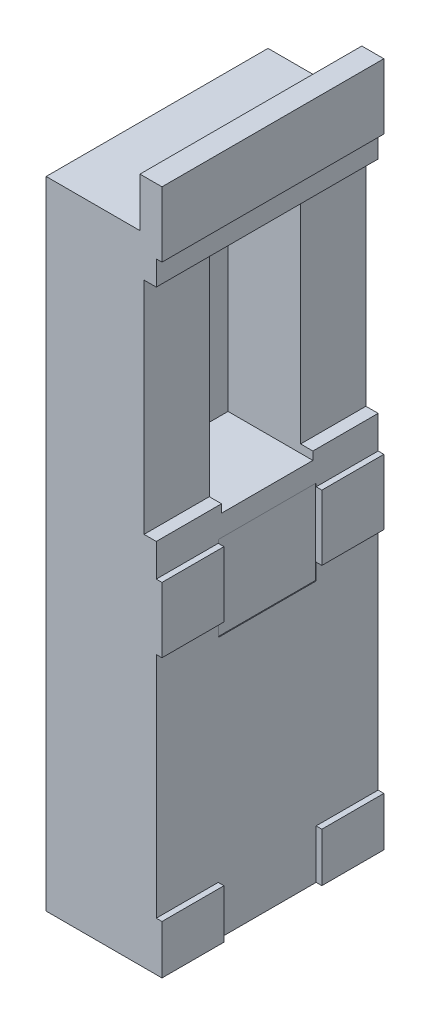
SolidWorks part; units mm, degrees
ref_plane "前视基准面" through (0, 0, 0) normal (0, 0, 1) x (1, 0, 0)
ref_plane "上视基准面" through (0, 0, 0) normal (0, 1, 0) x (1, 0, 0)
ref_plane "右视基准面" through (0, 0, 0) normal (1, 0, 0) x (0, 0, -1)
other "Configuration Table"
sketch "草图1" plane through (0, 0, 0) normal (0, 0, 1) x (1, 0, 0)
  line L0 (-10.2, 0) -> (-16.95, 0)
  line L1 (-16.95, 0) -> (-16.95, 54)
  line L2 (-16.95, 54) -> (-11.2, 54)
  line L3 (-11.2, 54) -> (-11.2, 57)
  line L4 (-11.2, 57) -> (-4.7, 57)
  line L5 (-4.7, 57) -> (-4.7, 53)
  line L6 (-4.7, 53) -> (-10.2, 53)
  line L7 (-10.2, 53) -> (-10.2, 51.5)
  line L8 (-10.2, 51.5) -> (-10.95, 51.5)
  line L9 (-10.95, 51.5) -> (-10.95, 38)
  line L10 (-10.95, 38) -> (-10.2, 38)
  line L11 (-10.2, 38) -> (-10.2, 36)
  line L12 (-10.2, 36) -> (-4.7, 36)
  line L13 (-4.7, 36) -> (-4.7, 32)
  line L14 (-4.7, 32) -> (-10.2, 32)
  line L15 (-10.2, 32) -> (-10.2, 0)
  dimension "x0" = 10.2
  dimension "x1" = 16.95
  dimension "x3" = 11.2
  dimension "x5" = 4.7
  dimension "x7" = 10.2
  dimension "x9" = 10.95
  dimension "x11" = 10.2
  dimension "x13" = 4.7
  dimension "y2" = 54
  dimension "y4" = 57
  dimension "y6" = 53
  dimension "y8" = 51.5
  dimension "y10" = 38
  dimension "y12" = 36
  dimension "y14" = 32
extrude "Guide_and_solid_stops" add sketch "草图1" along normal blind 13.6
ref_plane "Channel_midplane" through (0, 0, 6.8) normal (0, 0, 1) x (1, 0, 0)
sketch "草图3" plane through (0, 0, 6.8) normal (0, 0, 1) x (1, 0, 0)
  line L0 (-7, 37.5) -> (-15.4, 37.5)
  line L1 (-15.4, 37.5) -> (-15.4, 51.5)
  line L2 (-15.4, 51.5) -> (-7, 51.5)
  line L3 (-7, 51.5) -> (-7, 37.5)
  dimension "x0" = 7
  dimension "x1" = 15.4
  dimension "y0" = 37.5
  dimension "y2" = 51.5
extrude "Nut_tongue_channel" cut sketch "草图3" against normal mid plane 5.6
sketch "草图4" plane through (0, 0, 6.8) normal (0, 0, 1) x (1, 0, 0)
  line L0 (-4, 31) -> (-10.25, 31)
  line L1 (-10.25, 31) -> (-10.25, 36.2)
  line L2 (-10.25, 36.2) -> (-4, 36.2)
  line L3 (-4, 36.2) -> (-4, 31)
  dimension "x0" = 4
  dimension "x1" = 10.25
  dimension "y0" = 31
  dimension "y2" = 36.2
extrude "Lower_yoke_relief" cut sketch "草图4" against normal mid plane 6
sketch "草图5" plane through (0, 0, 0) normal (0, 0, 1) x (1, 0, 0)
  line L0 (-7.5, 15) -> (-11.2, 15)
  line L1 (-11.2, 15) -> (-11.2, 18)
  line L2 (-11.2, 18) -> (-7.5, 18)
  line L3 (-7.5, 18) -> (-7.5, 15)
  dimension "x0" = 7.5
  dimension "x1" = 11.2
  dimension "y0" = 15
  dimension "y2" = 18
extrude "Lower_inward_stop" add sketch "草图5" along normal blind 3.8
ref_plane "Lower_stop_rear_plane" through (0, 0, 9.8) normal (0, 0, 1) x (1, 0, 0)
sketch "草图7" plane through (0, 0, 9.8) normal (0, 0, 1) x (1, 0, 0)
  line L0 (-7.5, 15) -> (-11.2, 15)
  line L1 (-11.2, 15) -> (-11.2, 18)
  line L2 (-11.2, 18) -> (-7.5, 18)
  line L3 (-7.5, 18) -> (-7.5, 15)
  dimension "x0" = 7.5
  dimension "x1" = 11.2
  dimension "y0" = 15
  dimension "y2" = 18
extrude "凸台-拉伸2" add sketch "草图7" along normal blind 3.8
sketch "草图8" plane through (0, 0, 0) normal (0, 0, 1) x (1, 0, 0)
  line L0 (-3, -2) -> (-20, -2)
  line L1 (-20, -2) -> (-20, 15)
  line L2 (-20, 15) -> (-3, 15)
  line L3 (-3, 15) -> (-3, -2)
  dimension "x0" = 3
  dimension "x1" = 20
  dimension "y0" = 2
  dimension "y2" = 15
extrude "Remove_lower_tail" cut sketch "草图8" against normal through all and the other way through all
sketch "草图9" plane through (0, 0, 0) normal (0, 0, 1) x (1, 0, 0)
  line L0 (0, 13) -> (-9.85, 13)
  line L1 (-9.85, 13) -> (-9.85, 59)
  line L2 (-9.85, 59) -> (0, 59)
  line L3 (0, 59) -> (0, 13)
  dimension "x1" = 9.85
  dimension "y0" = 13
  dimension "y2" = 59
extrude "Wider_shaft_relief" cut sketch "草图9" against normal through all and the other way through all
